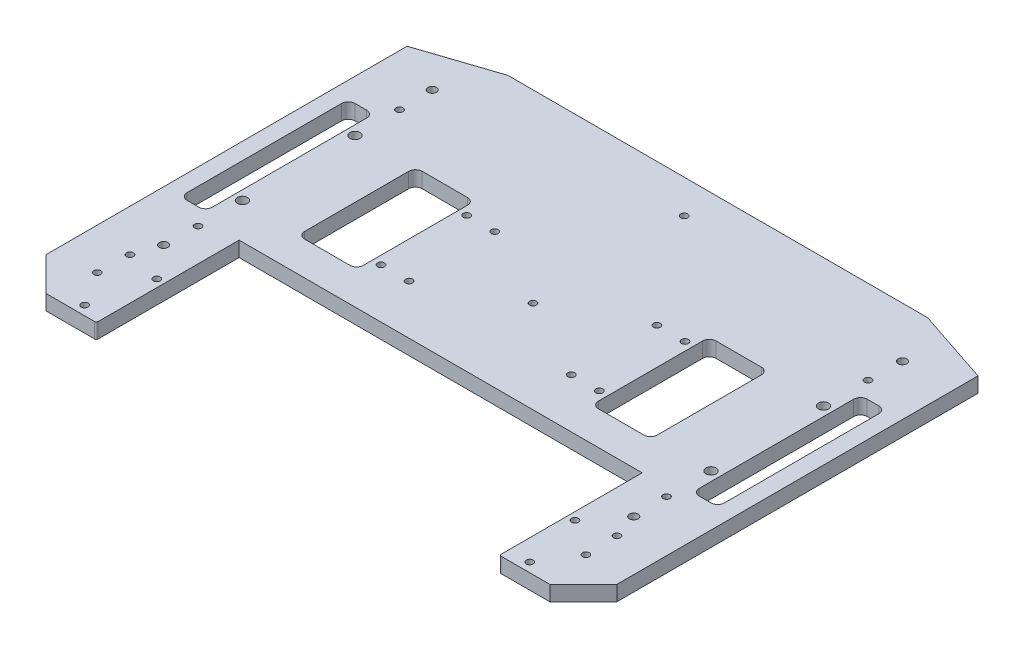
SolidWorks part; units mm, degrees
ref_plane "Plan de face" through (0, 0, 0) normal (0, 0, 1) x (1, 0, 0)
ref_plane "Plan de dessus" through (0, 0, 0) normal (0, 1, 0) x (1, 0, 0)
ref_plane "Plan de droite" through (0, 0, 0) normal (1, 0, 0) x (0, 0, -1)
sketch "Esquisse3" plane through (0, 0, 0) normal (0, 1, 0) x (1, 0, 0)
  line L0 (-281.7629, 0) -> (308.2067, 0) construction
  line L1 (0, 166.4902) -> (0, -269.1166) construction
  line L4 (-160, -46) -> (-160, 46)
  line L5 (-156, 50) -> (-149, 50)
  line L6 (-145, 46) -> (-145, -46)
  line L7 (-105, 0) -> (-105, 31)
  line L8 (-101, 35) -> (-74, 35)
  line L9 (-70, 31) -> (-70, -31)
  line L11 (-105, 0) -> (-105, -31)
  line L12 (-101, -35) -> (-74, -35)
  line L13 (-156, -50) -> (-149, -50)
  line L17 (156, 50) -> (149, 50)
  line L18 (156, -50) -> (149, -50)
  line L19 (145, 46) -> (145, -46)
  line L20 (160, -46) -> (160, 46)
  line L21 (105, 0) -> (105, 31)
  line L22 (101, -35) -> (74, -35)
  line L23 (105, 0) -> (105, -31)
  line L24 (70, 31) -> (70, -31)
  line L25 (101, 35) -> (74, 35)
  line L26 (125, 110) -> (-125, 110)
  line L34 (-170, 95) -> (-125, 110)
  line L35 (170, 95) -> (125, 110)
  line L38 (-170, 95) -> (-170, 0)
  line L39 (-170, 0) -> (-170, -120)
  line L40 (170, -120) -> (170, 0)
  line L41 (170, 0) -> (170, 95)
  line L43 (-170, -120) -> (-150, -140)
  line L44 (150, -140) -> (170, -120)
  line L45 (-150, -140) -> (-120, -140)
  line L46 (-120, -140) -> (-120, -55)
  line L47 (-120, -55) -> (120, -55)
  line L48 (120, -55) -> (120, -140)
  line L49 (120, -140) -> (150, -140)
  line L50 (-170, 95) -> (170, 95) construction
  line L51 (-170, 0) -> (-220, 0) construction
  line L52 (-220, 0) -> (-170, 95) construction
  line L53 (-220, 0) -> (-170, -120) construction
  line L54 (-130, -140) -> (-130, -220) construction
  line L55 (-130, -220) -> (130, -220) construction
  line L56 (130, -140) -> (130, -220) construction
  line L57 (-170, -120) -> (-130, -220) construction
  arc A0 (-149, 50) -> (-145, 46) centre (-149, 46) cw
  arc A1 (-74, 35) -> (-70, 31) centre (-74, 31) cw
  arc A2 (-105, 31) -> (-101, 35) centre (-101, 31) cw
  arc A3 (-160, 46) -> (-156, 50) centre (-156, 46) cw
  arc A4 (-105, -31) -> (-101, -35) centre (-101, -31) ccw
  arc A5 (-74, -35) -> (-70, -31) centre (-74, -31) ccw
  arc A6 (-160, -46) -> (-156, -50) centre (-156, -46) ccw
  arc A7 (-149, -50) -> (-145, -46) centre (-149, -46) ccw
  arc A8 (149, 50) -> (145, 46) centre (149, 46) ccw
  arc A9 (160, 46) -> (156, 50) centre (156, 46) ccw
  arc A10 (149, -50) -> (145, -46) centre (149, -46) cw
  arc A11 (160, -46) -> (156, -50) centre (156, -46) cw
  arc A12 (74, -35) -> (70, -31) centre (74, -31) cw
  arc A13 (105, -31) -> (101, -35) centre (101, -31) cw
  arc A14 (105, 31) -> (101, 35) centre (101, 31) ccw
  arc A15 (74, 35) -> (70, 31) centre (74, 31) ccw
  circle A16 centre (-140, 80) radius 2.55
  circle A17 centre (-140, -80) radius 2.55
  circle A18 centre (140, -80) radius 2.55
  circle A19 centre (140, 80) radius 2.55
  point P6 (-170, 110)
  point P16 (-105, 15.5)
  point P19 (-145, 50)
  point P22 (-70, 35)
  point P25 (-105, 35)
  point P28 (-160, 50)
  point P32 (-70, 0)
  point P37 (-105, -35)
  point P38 (-70, -35)
  point P40 (-145, 0)
  point P41 (-160, 0)
  point P45 (-160, -50)
  point P46 (-145, -50)
  point P47 (0, 110)
  point P48 (-170, 0)
  point P51 (0, -110)
  point P64 (145, -50)
  point P65 (160, -50)
  point P75 (70, -35)
  point P76 (105, -35)
  point P81 (105, 35)
  point P82 (70, 35)
  point P83 (0, -269.1166)
  point P85 (0, 110)
  point P94 (-170, 0)
  point P97 (170, 0)
  point P100 (0, -130)
  dimension "D7" = 4
  dimension "D10" = 5.1
  dimension "D2" = 250
  dimension "D3" = 35
  dimension "D4" = 15
  dimension "D5" = 70
  dimension "D6" = 40
  dimension "D14" = 30
  dimension "D13" = 110
  dimension "D8" = 35
  dimension "D9" = 50
  dimension "D11" = 240
  dimension "D12" = 340
  dimension "D15" = 120
  dimension "D16" = 95
  dimension "D17" = 140
  dimension "D18" = 80
  dimension "D19" = 85
  dimension "D20" = 140
  dimension "D21" = 125
  dimension "D22" = 28.2843
  dimension "D23" = 47.4342
  dimension "D24" = 120
  dimension "D25" = 50
  dimension "D26" = 130
  dimension "D27" = 107.3546
  dimension "D28" = 80
  dimension "D29" = 10
  dimension "D30" = 107.7033
  dimension "D31" = 130
extrude "structure" add sketch "Esquisse3" against normal blind 9
sketch "Esquisse4" plane through (0, 0, 0) normal (0, 1, 0) x (1, 0, 0)
  line L0 (-232.6304, 0) -> (230.9735, 0) construction
  line L1 (0, 112.1729) -> (0, -129.4048) construction
  line L3 (-145, -46) -> (-145, 46) construction
  line L12 (-125, 110) -> (-170, 95)
  line L13 (-170, 95) -> (-170, -120)
  line L14 (-170, -120) -> (-150, -140)
  line L15 (-120, -55) -> (120, -55)
  line L16 (150, -140) -> (170, -120)
  line L17 (170, -120) -> (170, 95)
  line L18 (170, 95) -> (125, 110)
  line L19 (125, 110) -> (-125, 110)
  line L20 (-125, 110) -> (-170, 95)
  line L21 (-170, 95) -> (-170, -120)
  line L22 (-170, -120) -> (-150, -140)
  line L24 (150, -140) -> (170, -120)
  line L25 (170, -120) -> (170, 95)
  line L26 (170, 95) -> (125, 110)
  line L27 (125, 110) -> (-125, 110)
  line L32 (-120, -55) -> (120, -55)
  line L33 (120, -55) -> (120, -140)
  line L34 (120, -55) -> (120, -140)
  line L35 (120, -140) -> (150, -140)
  line L36 (120, -140) -> (150, -140)
  line L37 (-150, -140) -> (-120, -140)
  line L38 (-150, -140) -> (-120, -140)
  line L39 (-120, -140) -> (-120, -55)
  line L40 (-120, -140) -> (-120, -55)
  circle A0 centre (-139.5, 33.5) radius 3.05
  circle A2 centre (-139.5, -33.5) radius 3.05
  circle A3 centre (139.5, -33.5) radius 3.05
  circle A4 centre (139.5, 33.5) radius 3.05
  dimension "D1" = 6.1
  dimension "D2" = 0
  dimension "D3" = 33.5
  dimension "D4" = 5.5
extrude "encoches_tiges" cut sketch "Esquisse4" against normal blind 5 contours A3 | A4 | A2 | A0
sketch "Esquisse5" plane through (0, 0, 0) normal (0, 1, 0) x (1, 0, 0)
  line L0 (-244.8916, 0) -> (242.9033, 0) construction
  line L1 (0, 111.8416) -> (0, -134.3756) construction
  line L3 (-145, -46) -> (-145, 46) construction
  line L12 (-125, 110) -> (-170, 95)
  line L13 (-170, 95) -> (-170, -120)
  line L14 (-170, -120) -> (-150, -140)
  line L15 (-120, -55) -> (120, -55)
  line L16 (150, -140) -> (170, -120)
  line L17 (170, -120) -> (170, 95)
  line L18 (170, 95) -> (125, 110)
  line L19 (125, 110) -> (-125, 110)
  line L20 (-125, 110) -> (-170, 95)
  line L21 (-170, 95) -> (-170, -120)
  line L22 (-170, -120) -> (-150, -140)
  line L24 (150, -140) -> (170, -120)
  line L25 (170, -120) -> (170, 95)
  line L26 (170, 95) -> (125, 110)
  line L27 (125, 110) -> (-125, 110)
  line L32 (-120, -55) -> (120, -55)
  line L33 (120, -55) -> (120, -140)
  line L34 (120, -55) -> (120, -140)
  line L35 (120, -140) -> (150, -140)
  line L36 (120, -140) -> (150, -140)
  line L37 (-150, -140) -> (-120, -140)
  line L38 (-150, -140) -> (-120, -140)
  line L39 (-120, -140) -> (-120, -55)
  line L40 (-120, -140) -> (-120, -55)
  circle A0 centre (-139.5, 60) radius 2.05
  circle A1 centre (-139.5, -60) radius 2.05
  circle A2 centre (139.5, -60) radius 2.05
  circle A3 centre (139.5, 60) radius 2.05
  dimension "D3" = 4.1
  dimension "D1" = 60
  dimension "D2" = 0
  dimension "D4" = 5.5
extrude "encodeurs" cut sketch "Esquisse5" against normal through all contours A1 | A0 | A3 | A2
sketch "Esquisse6" plane through (0, 0, 0) normal (0, 1, 0) x (1, 0, 0)
  line L0 (0, 109.8533) -> (0, -117.4751) construction
  line L1 (-179.2779, 0) -> (195.847, 0) construction
  line L2 (-98.5767, 25.5) -> (7.2216, 25.5) construction
  line L4 (-70, -31) -> (-70, 31) construction
  line L12 (-125, 110) -> (-170, 95)
  line L13 (-170, 95) -> (-170, -120)
  line L14 (-170, -120) -> (-150, -140)
  line L15 (-120, -55) -> (120, -55)
  line L16 (150, -140) -> (170, -120)
  line L17 (170, -120) -> (170, 95)
  line L18 (170, 95) -> (125, 110)
  line L19 (125, 110) -> (-125, 110)
  line L20 (-125, 110) -> (-170, 95)
  line L21 (-170, 95) -> (-170, -120)
  line L22 (-170, -120) -> (-150, -140)
  line L24 (150, -140) -> (170, -120)
  line L25 (170, -120) -> (170, 95)
  line L26 (170, 95) -> (125, 110)
  line L27 (125, 110) -> (-125, 110)
  line L33 (-120, -55) -> (120, -55)
  line L34 (120, -55) -> (120, -140)
  line L35 (120, -55) -> (120, -140)
  line L36 (120, -140) -> (150, -140)
  line L37 (120, -140) -> (150, -140)
  line L38 (-150, -140) -> (-120, -140)
  line L39 (-150, -140) -> (-120, -140)
  line L40 (-120, -140) -> (-120, -55)
  line L41 (-120, -140) -> (-120, -55)
  circle A0 centre (-65, 25.5) radius 2.05
  circle A1 centre (-48.3, 25.5) radius 2.05
  circle A2 centre (-48.3, -25.5) radius 2.05
  circle A3 centre (-65, -25.5) radius 2.05
  circle A4 centre (65, -25.5) radius 2.05
  circle A5 centre (48.3, -25.5) radius 2.05
  circle A6 centre (48.3, 25.5) radius 2.05
  circle A7 centre (65, 25.5) radius 2.05
  dimension "D1" = 4.1
  dimension "D2" = 4.1
  dimension "D3" = 16.7
  dimension "D4" = 25.5
  dimension "D5" = 0
  dimension "D6" = 5
extrude "moteurs" cut sketch "Esquisse6" against normal through all both and the other way through all contours A0 | A1 | A3 | A5 | A4 | A2 | A6 | A7
sketch "Esquisse7" plane through (0, 0, 0) normal (0, 1, 0) x (1, 0, 0)
  line L0 (-174.1619, -95) -> (241.5194, -95) construction
  line L2 (0, -145.9077) -> (0, 135.7674) construction
  line L3 (-194.9191, 0) -> (209.9418, 0) construction
  circle A0 centre (0, 90) radius 2.05
  circle A1 centre (0, -90) radius 2.05 construction
  circle A2 centre (0, 0) radius 2.05
  circle A3 centre (-145, -95) radius 2.05
  circle A4 centre (145, -95) radius 2.05
  dimension "D1" = 4.1
  dimension "D3" = 4.1
  dimension "D5" = 145
  dimension "D2" = 90
  dimension "D4" = 95
extrude "patins" cut sketch "Esquisse7" against normal through all
sketch "Esquisse8" plane through (0, 0, 0) normal (0, 1, 0) x (1, 0, 0)
  line L0 (0, 136.7319) -> (0, -163.5964) construction
  line L13 (-120, -55) -> (120, -55)
  line L14 (-120, -55) -> (120, -55)
  line L15 (120, -55) -> (120, -140)
  line L16 (120, -55) -> (120, -140)
  line L17 (120, -140) -> (150, -140)
  line L18 (120, -140) -> (150, -140)
  line L19 (150, -140) -> (170, -120)
  line L20 (150, -140) -> (170, -120)
  line L21 (170, -120) -> (170, 95)
  line L22 (170, -120) -> (170, 95)
  line L23 (170, 95) -> (125, 110)
  line L24 (170, 95) -> (125, 110)
  line L37 (125, 110) -> (-125, 110)
  line L38 (125, 110) -> (-125, 110)
  line L39 (-125, 110) -> (-170, 95)
  line L40 (-125, 110) -> (-170, 95)
  line L41 (-170, 95) -> (-170, -120)
  line L42 (-170, 95) -> (-170, -120)
  line L43 (-170, -120) -> (-150, -140)
  line L44 (-170, -120) -> (-150, -140)
  line L45 (-150, -140) -> (-120, -140)
  line L46 (-150, -140) -> (-120, -140)
  line L47 (-120, -140) -> (-120, -55)
  line L48 (-120, -140) -> (-120, -55)
  circle A0 centre (-132.5, -134.5) radius 2.05
  circle A1 centre (-124.5, -99.5) radius 2.05
  circle A2 centre (132.5, -134.5) radius 2.05
  circle A3 centre (124.5, -99.5) radius 2.05
  circle A4 centre (-145.5, -114) radius 2.05
  circle A5 centre (145.5, -114) radius 2.05
  dimension "D2" = 4.1
  dimension "D7" = 40.5
  dimension "D1" = 0
  dimension "D3" = 4.5
  dimension "D4" = 26
  dimension "D5" = 5.5
  dimension "D6" = 25.5
  dimension "D8" = 12.5
extrude "actionneurs" cut sketch "Esquisse8" against normal through all contours A1 | A0 | A3 | A2 | A4 | A5
fillet "Congé1" radius 1 2 edges at (120, -4.5, 140) (-120, -4.5, 140)
